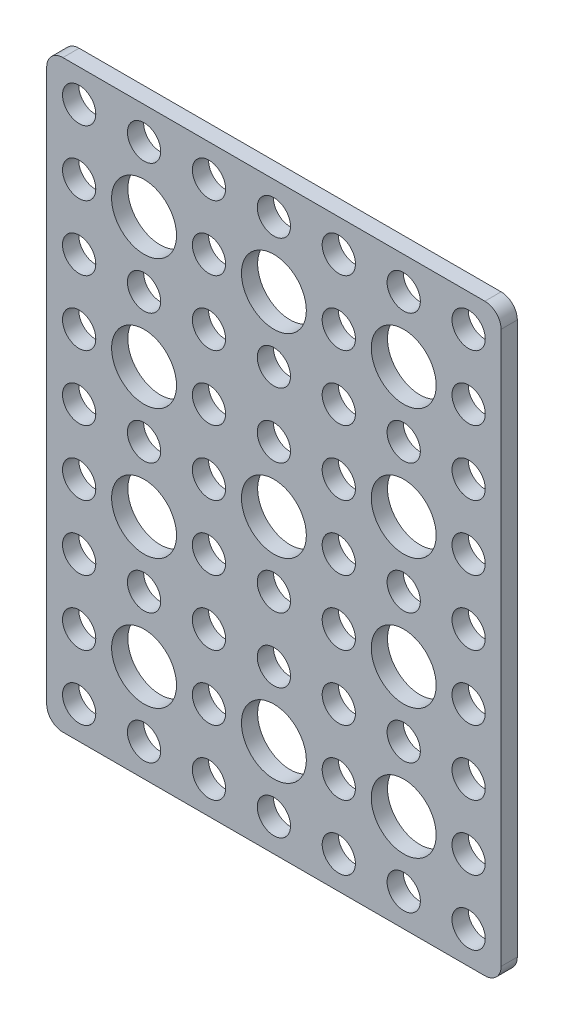
SolidWorks part; units mm, degrees
ref_plane "Front Plane" through (0, 0, 0) normal (0, 0, 1) x (1, 0, 0)
ref_plane "Top Plane" through (0, 0, 0) normal (0, 1, 0) x (1, 0, 0)
ref_plane "Right Plane" through (0, 0, 0) normal (1, 0, 0) x (0, 0, -1)
sketch "Sketch1" plane through (0, 0, 0) normal (0, 0, 1) x (1, 0, 0)
  line L1 (0, 0) -> (56, 0)
  line L2 (0, 0) -> (0, 72)
  line L3 (0, 72) -> (56, 72)
  line L4 (56, 0) -> (56, 72)
  dimension "D1" = 56
  dimension "D2" = 72
extrude "Boss-Extrude1" add sketch "Sketch1" along normal blind 2
sketch "Sketch2" plane through (0, 0, 2) normal (0, 0, 1) x (1, 0, 0)
  line L0 (56, 72) -> (0, 72) construction
  line L1 (0, 72) -> (0, 0) construction
  circle A0 centre (4, 68) radius 2.05
  dimension "D1" = 4.1
  dimension "D2" = 4
  dimension "D3" = 4
extrude "Cut-Extrude1" cut sketch "Sketch2" against normal through all
pattern_linear "LPattern1" count 7 spacing 8 along (1, 0, 0) count 9 spacing 8 along (0, -1, 0) skipping (1, 1), (1, 3), (1, 5), (1, 7), (3, 1), (3, 4), (3, 7), (5, 1), (5, 3), (5, 5), (5, 7) of "Cut-Extrude1"
fillet "Fillet1" radius 2 4 edges at (0, 0, 1) (56, 0, 1) (56, 72, 1) (0, 72, 1)
sketch "Sketch3" plane through (0, 0, 2) normal (0, 0, 1) x (1, 0, 0)
  circle A0 centre (12, 60) radius 4
  circle A1 centre (12, 68) radius 2.05 construction
  circle A2 centre (4, 60) radius 2.05 construction
  dimension "D1" = 8
  dimension "D3" = 8
  dimension "D2" = 8
extrude "Cut-Extrude2" cut sketch "Sketch3" against normal through all
pattern_linear "LPattern2" count 3 spacing 16 along (1, 0, 0) count 4 spacing 16 along (0, -1, 0) skipping (1, 1), (1, 2) of "Cut-Extrude2"
sketch "Sketch4" plane through (0, 0, 2) normal (0, 0, 1) x (1, 0, 0)
  circle A0 centre (28, 36) radius 4
  circle A1 centre (28, 44) radius 2.05 construction
  circle A2 centre (20, 36) radius 2.05 construction
  dimension "D3" = 8
  dimension "D1" = 8
  dimension "D2" = 8
extrude "Cut-Extrude3" cut sketch "Sketch4" against normal through all
